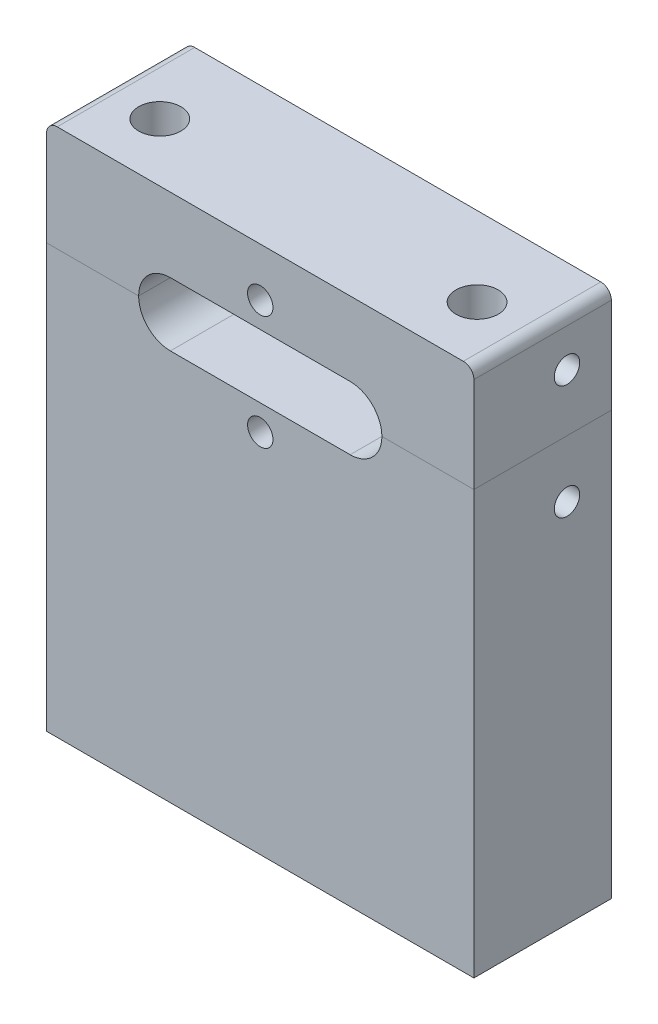
SolidWorks part; units mm, degrees
ref_plane "Front Plane" through (0, 0, 0) normal (0, 0, 1) x (1, 0, 0)
ref_plane "Top Plane" through (0, 0, 0) normal (0, 1, 0) x (1, 0, 0)
ref_plane "Right Plane" through (0, 0, 0) normal (1, 0, 0) x (0, 0, -1)
sketch "Sketch1" plane through (0, 0, 0) normal (0, 1, 0) x (1, 0, 0)
  line L1 (-12.827, -4.1275) -> (12.827, -4.1275)
  line L2 (-12.827, -4.1275) -> (-12.827, 4.1275)
  line L3 (-12.827, 4.1275) -> (12.827, 4.1275)
  line L4 (12.827, -4.1275) -> (12.827, 4.1275)
  line L5 (-12.827, -4.1275) -> (12.827, 4.1275) construction
  line L6 (-12.827, 4.1275) -> (12.827, -4.1275) construction
  point P0 (0, 0)
  dimension "D1" = 25.654
  dimension "D2" = 8.255
extrude "Boss-Extrude1" add sketch "Sketch1" along normal blind 31.75
sketch "Sketch2" plane through (0, 0, -4.1275) normal (0, 0, -1) x (-1, 0, 0)
  line L0 (5.3975, 25.4) -> (-5.3975, 25.4) construction
  line L1 (5.3975, 23.495) -> (-5.3975, 23.495)
  line L2 (5.3975, 27.305) -> (-5.3975, 27.305)
  line L3 (12.827, 25.4) -> (-12.827, 25.4) construction
  line L6 (12.827, 31.75) -> (12.827, 0) construction
  line L7 (-12.827, 31.75) -> (-12.827, 0) construction
  line L9 (-12.827, 31.75) -> (12.827, 31.75) construction
  arc A0 (5.3975, 23.495) -> (5.3975, 27.305) centre (5.3975, 25.4) ccw
  arc A1 (-5.3975, 27.305) -> (-5.3975, 23.495) centre (-5.3975, 25.4) ccw
  point P2 (0, 25.4)
  dimension "D1" = 6.35
  dimension "D2" = 10.795
  dimension "D3" = 3.81
extrude "Cut-Extrude1" cut sketch "Sketch2" against normal blind 25.4
sketch "Sketch8" plane through (0, 0, 4.1275) normal (0, 0, 1) x (1, 0, 0)
  line L0 (-12.827, 0) -> (12.827, 0) construction
  line L5 (-7.3025, 25.4) -> (7.3025, 25.4) construction
  line L8 (5.588, 31.75) -> (5.588, 0) construction
  line L9 (-12.827, 31.75) -> (12.827, 31.75) construction
  circle A0 centre (0, 28.829) radius 0.762
  circle A1 centre (0, 21.971) radius 0.762
  arc A2 (-5.3975, 27.305) -> (-5.3975, 23.495) centre (-5.3975, 25.4) ccw construction
  arc A3 (5.3975, 23.495) -> (5.3975, 27.305) centre (5.3975, 25.4) ccw construction
  point P7 (0, 31.75)
  dimension "D1" = 1.524
  dimension "D2" = 5.588
  dimension "D4" = 3.429
revolve "Cut-Revolve1" cut sketch "Sketch8" angle 90 about L8
sketch "Sketch9" plane through (12.827, 0, 0) normal (1, 0, 0) x (0, 0, -1)
  circle A0 centre (1.4605, 28.829) radius 0.762 construction
  circle A1 centre (1.4605, 21.971) radius 0.762 construction
  circle A2 centre (1.4605, 28.829) radius 0.762
  circle A3 centre (1.4605, 21.971) radius 0.762
extrude "Cut-Extrude4" cut sketch "Sketch9" against normal up to next
fillet "Fillet1" radius 0.635 2 edges at (-12.827, 31.75, 0) (12.827, 31.75, 0)
sketch "Sketch10" plane through (0, 31.75, 0) normal (0, 1, 0) x (1, 0, 0)
  line L0 (0, 0) -> (0, 5.1997) construction
  circle A0 centre (9.525, -0.635) radius 1.27
  circle A1 centre (-9.525, -0.635) radius 1.27
  dimension "D1" = 9.525
  dimension "D2" = 2.54
  dimension "D3" = 0.635
extrude "Cut-Extrude5" cut sketch "Sketch10" against normal blind 12.7
ref_plane "SplitPlane" through (0, 25.4, 0) normal (0, 1, 0) x (1, 0, 0)
split "Split1" trim tools "SplitPlane" bodies to split 111 resulting bodies 112 113
